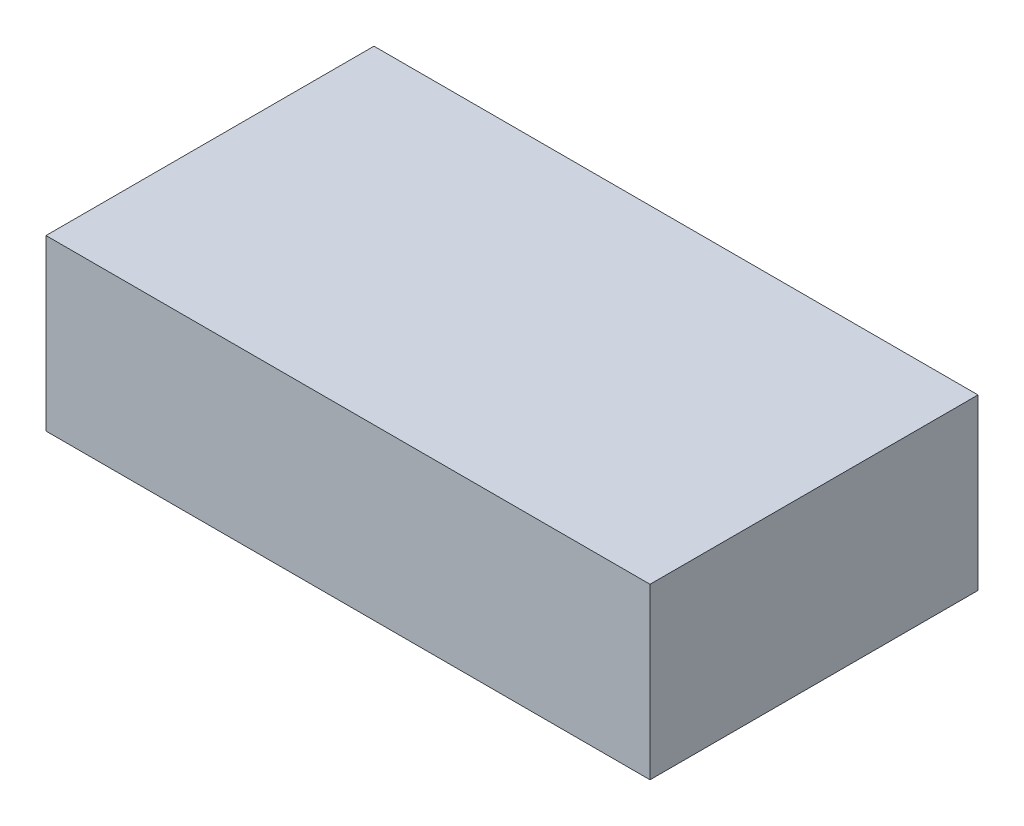
SolidWorks part; units mm, degrees
ref_plane "Plan de face" through (0, 0, 0) normal (0, 0, 1) x (1, 0, 0)
ref_plane "Plan de dessus" through (0, 0, 0) normal (0, 1, 0) x (1, 0, 0)
ref_plane "Plan de droite" through (0, 0, 0) normal (1, 0, 0) x (0, 0, -1)
sketch "Esquisse1" plane through (0, 0, 0) normal (0, 1, 0) x (1, 0, 0)
  line L0 (38.215, 0) -> (-38.215, 0)
  line L1 (38.215, 0) -> (38.215, 41.5)
  line L2 (38.215, 41.5) -> (-38.215, 41.5)
  line L3 (-38.215, 41.5) -> (-38.215, 0)
  point P0 (38.5625, 0)
  point P3 (0, 0)
  point P8 (-37.8298, 0)
extrude "Boss.-Extru.1" add sketch "Esquisse1" along normal blind 21.43 contours L0 L3 L2 L1
